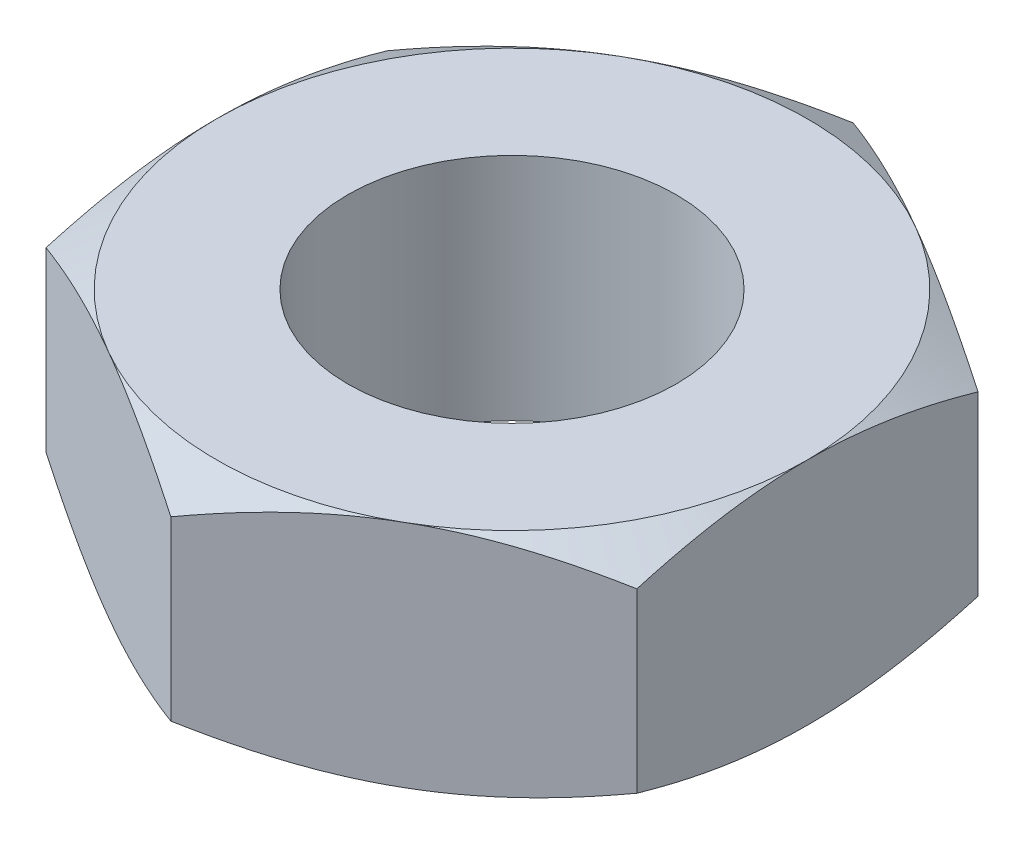
SolidWorks part; units mm, degrees
ref_plane "Front Plane" through (0, 0, 0) normal (0, 0, 1) x (1, 0, 0)
ref_plane "Top Plane" through (0, 0, 0) normal (0, 1, 0) x (1, 0, 0)
ref_plane "Right Plane" through (0, 0, 0) normal (1, 0, 0) x (0, 0, -1)
sketch "Sketch1" plane through (0, 0, 0) normal (0, 1, 0) x (1, 0, 0)
  line L1 (0, -2.5981) -> (2.25, -1.299)
  line L2 (2.25, -1.299) -> (2.25, 1.299)
  line L3 (2.25, 1.299) -> (0, 2.5981)
  line L4 (0, 2.5981) -> (-2.25, 1.299)
  line L5 (-2.25, 1.299) -> (-2.25, -1.299)
  line L6 (-2.25, -1.299) -> (0, -2.5981)
  circle A0 centre (0, 0) radius 1.25
  circle A1 centre (0, 0) radius 2.25 construction
  dimension "D1" = 2.5
  dimension "D2" = 4.5
extrude "Boss-Extrude1" add sketch "Sketch1" along normal blind 1.75
sketch "Sketch2" plane through (0, 1.75, 0) normal (0, 1, 0) x (1, 0, 0)
  circle A0 centre (0, 0) radius 2.25 construction
  circle A1 centre (0, 0) radius 2.25
extrude "Cut-Extrude1" cut sketch "Sketch2" against normal blind 2 draft 60 flip side to cut
sketch "Sketch3" plane through (0, 0, 0) normal (0, -1, 0) x (1, 0, 0)
  circle A0 centre (0, 0) radius 2.25 construction
  circle A1 centre (0, 0) radius 2.25
extrude "Cut-Extrude2" cut sketch "Sketch3" against normal blind 2 draft 60 flip side to cut
